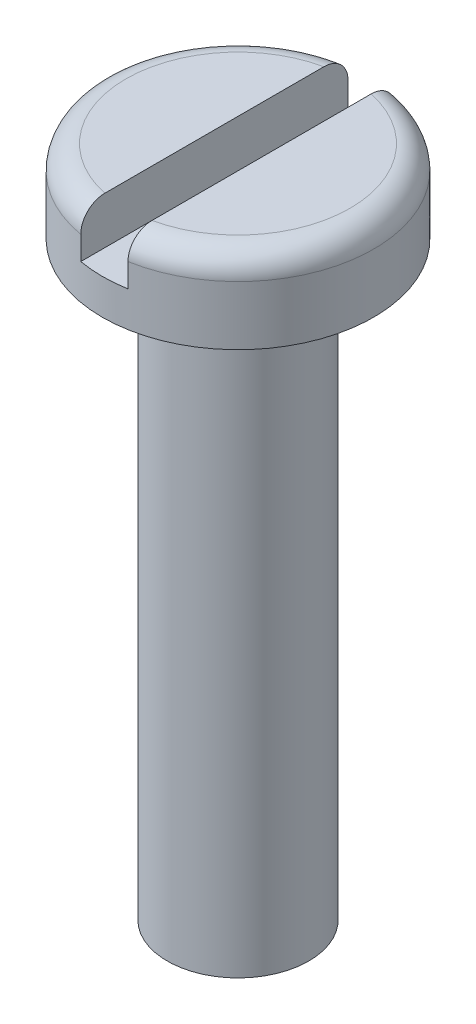
SolidWorks part; units mm, degrees
ref_plane "Front Plane" through (0, 0, 0) normal (0, 0, 1) x (1, 0, 0)
ref_plane "Top Plane" through (0, 0, 0) normal (0, 1, 0) x (1, 0, 0)
ref_plane "Right Plane" through (0, 0, 0) normal (1, 0, 0) x (0, 0, -1)
sketch "Sketch1" plane through (0, 0, 0) normal (0, 1, 0) x (1, 0, 0)
  circle A0 centre (0, 0) radius 5.75
  dimension "D1" = 11.5
extrude "Boss-Extrude1" add sketch "Sketch1" along normal blind 3.5
sketch "Sketch2" plane through (0, 0, 0) normal (0, -1, 0) x (1, 0, 0)
  circle A0 centre (0, 0) radius 3
  dimension "D1" = 6
extrude "Boss-Extrude2" add sketch "Sketch2" along normal blind 25
fillet "Fillet1" radius 1 1 edges at (0, 3.5, 5.75)
sketch "Sketch3" plane through (0, 3.5, 0) normal (0, 1, 0) x (1, 0, 0)
  line L1 (-1, 6.5684) -> (1, 6.5684)
  line L2 (-1, 6.5684) -> (-1, -6.5684)
  line L3 (-1, -6.5684) -> (1, -6.5684)
  line L4 (1, 6.5684) -> (1, -6.5684)
  line L5 (-1, 6.5684) -> (1, -6.5684) construction
  line L6 (-1, -6.5684) -> (1, 6.5684) construction
  point P0 (0, 0)
  dimension "D1" = 2
extrude "Cut-Extrude1" cut sketch "Sketch3" against normal blind 2
